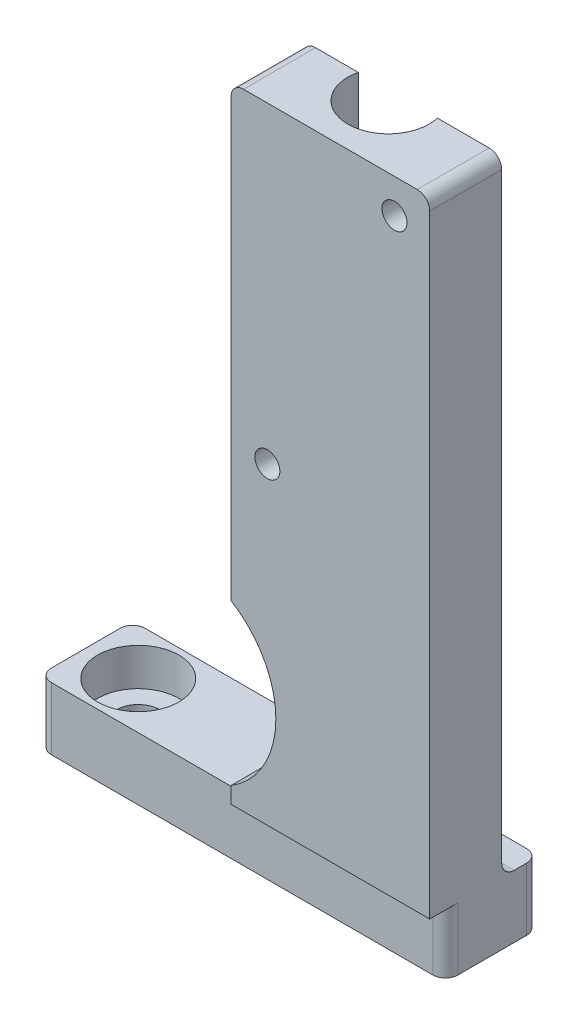
SolidWorks part; units mm, degrees
ref_plane "Front Plane" through (0, 0, 0) normal (0, 0, 1) x (1, 0, 0)
ref_plane "Top Plane" through (0, 0, 0) normal (0, 1, 0) x (1, 0, 0)
ref_plane "Right Plane" through (0, 0, 0) normal (1, 0, 0) x (0, 0, -1)
sketch "Sketch1" plane through (0, 0, 0) normal (0, 0, 1) x (1, 0, 0)
  line L1 (0, 0) -> (32.5, 0)
  line L2 (0, 0) -> (0, 5)
  line L3 (0, 5) -> (16.62, 5)
  line L4 (32.5, 0) -> (32.5, 4.2398)
  line L6 (32.5, 4.2398) -> (32.5, 55)
  line L7 (32.5, 55) -> (16.62, 55)
  line L8 (16.62, 5) -> (16.62, 55)
  dimension "D1" = 32.5
  dimension "D2" = 5
  dimension "D3" = 50
  dimension "D4" = 15.88
extrude "Boss-Extrude1" add sketch "Sketch1" along normal blind 8.75
hole_wizard "M3 Clearance Hole1" positions "Sketch3" profile "Sketch4" hole size "M3" standard "ANSI Metric" end condition up to next
sketch "Sketch3" plane through (0, 0, 8.75) normal (0, 0, 1) x (1, 0, 0)
  point P0 (29.68, 52.275)
  point P3 (19.52, 30)
sketch "Sketch4" plane through (29.68, 52.275, 8.75) normal (1, 0, 0) x (0, -1, 0)
  line L0 (0, 0) -> (0, 8.75)
  line L1 (0, 8.75) -> (1, 8.75)
  line L2 (1, 8.75) -> (1, 0)
  line L5 (1, 0) -> (0, 0)
  line L11 (0, -6.35) -> (0, 107.95) construction
  dimension "Thru Hole Dia." = 2
  dimension "Thru Hole Depth" = 8.75
sketch "Sketch5" plane through (0, 0, 0) normal (-1, 0, 0) x (0, 0, 1)
  line L0 (8.75, 0) -> (0, 0) construction
  line L1 (8.75, 5) -> (7.5, 5)
  line L2 (8.75, 5) -> (8.75, 0)
  line L3 (8.75, 0) -> (7.5, 0)
  line L4 (7.5, 5) -> (7.5, 0)
  dimension "D1" = 1.25
extrude "Cut-Extrude2" cut sketch "Sketch5" against normal up to surface (32.5 mm away) up to face at (32.5, 27.5, 4.375)
sketch "Sketch7" plane through (0, 55, 0) normal (0, 1, 0) x (1, 0, 0)
  line L0 (32.5, -8.75) -> (32.5, 0) construction
  line L1 (16.62, 0) -> (32.5, 0)
  line L2 (16.62, 0) -> (16.62, -3)
  line L3 (16.62, -3) -> (32.5, -3)
  line L4 (32.5, 0) -> (32.5, -3)
  dimension "D1" = 3
extrude "Cut-Extrude4" cut sketch "Sketch7" against normal up to surface (50 mm away) up to face at (8.31, 5, 3.75)
hole_wizard "CBORE for M3 SHCS1" positions "Sketch8" profile "Sketch9" counterbore size "M3" standard "ANSI Metric" end condition up to next
sketch "Sketch8" plane through (0, 5, 0) normal (0, 1, 0) x (1, 0, 0)
  point P0 (4.2, -3.75)
sketch "Sketch9" plane through (4.2, 5, 3.75) normal (1, 0, 0) x (0, 0, 1)
  line L0 (0, 0) -> (0, 5)
  line L1 (0, 5) -> (1.7, 5)
  line L3 (1.7, 5) -> (1.7, 3)
  line L4 (1.7, 3) -> (3.25, 3)
  line L5 (3.25, 3) -> (3.25, 0)
  line L7 (3.25, 0) -> (0, 0)
  line L11 (0, -6.35) -> (0, 107.95) construction
  dimension "Thru Hole Dia." = 3.4
  dimension "Thru Hole Depth" = 5
  dimension "C'Bore Dia." = 6.5
  dimension "C'Bore Depth" = 3
fillet "Fillet1" radius 1 8 edges at (16.62, 5, 5.25) (24.56, 5, 3) (32.5, 2.5, 7.5) (32.5, 2.5, 0) (0, 2.5, 7.5) (0, 2.5, 0) (32.5, 55, 5.875) (16.62, 55, 5.875)
sketch "Sketch12" plane through (0, 0, 8.75) normal (0, 0, 1) x (1, 0, 0)
  circle A0 centre (12.7, 12.7) radius 7.5
  dimension "D1" = 15
extrude "Cut-Extrude5" cut sketch "Sketch12" against normal up to surface (5.75 mm away) up to face at (30.68, 52.275, 3)
hole_wizard "CBORE for M3 SHCS2" positions "Sketch13" profile "Sketch14" counterbore size "M3" standard "ANSI Metric" end condition up to next
sketch "Sketch13" plane through (0, 55, 0) normal (0, 1, 0) x (1, 0, 0)
  point P0 (24.2, -3.75)
sketch "Sketch14" plane through (24.2, 55, 3.75) normal (1, 0, 0) x (0, 0, 1)
  line L0 (0, 0) -> (0, 55)
  line L1 (0, 55) -> (1.7, 55)
  line L3 (1.7, 55) -> (1.7, 53)
  line L4 (1.7, 53) -> (3.25, 53)
  line L5 (3.25, 53) -> (3.25, 0)
  line L7 (3.25, 0) -> (0, 0)
  line L11 (0, -6.35) -> (0, 107.95) construction
  dimension "Thru Hole Dia." = 3.4
  dimension "Thru Hole Depth" = 55
  dimension "C'Bore Dia." = 6.5
  dimension "C'Bore Depth" = 53
